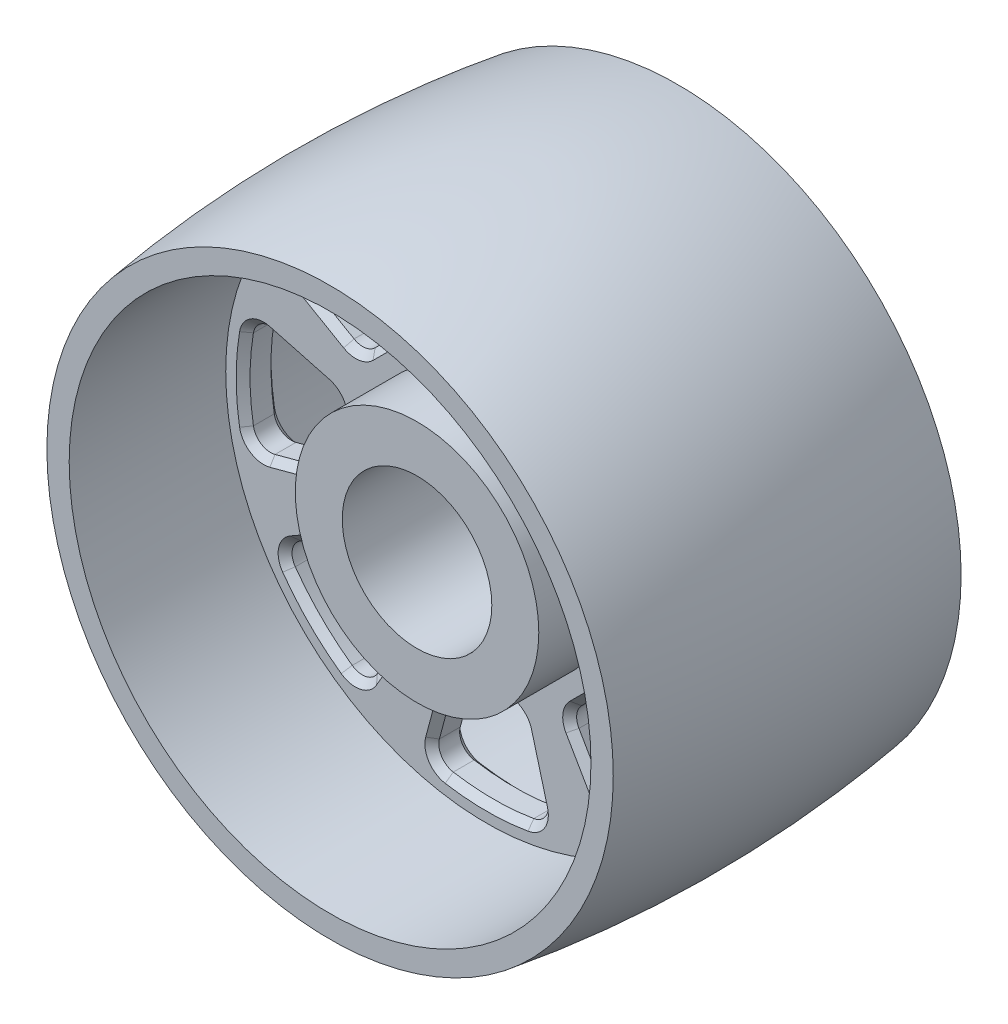
SolidWorks part; units mm, degrees
ref_plane "Front Plane" through (0, 0, 0) normal (0, 0, 1) x (1, 0, 0)
ref_plane "Top Plane" through (0, 0, 0) normal (0, 1, 0) x (1, 0, 0)
ref_plane "Right Plane" through (0, 0, 0) normal (1, 0, 0) x (0, 0, -1)
sketch "Sketch1" plane through (0, 0, 0) normal (1, 0, 0) x (0, 0, -1)
  line L0 (0, 0) -> (340.7129, 0) construction
  line L1 (0, 0) -> (0, 245.6893) construction
  line L2 (-50, 43) -> (50, 43)
  line L3 (-50, 43) -> (-50, 70)
  line L4 (-50, 70) -> (-10, 70)
  line L5 (-10, 70) -> (-10, 150)
  line L6 (-10, 150) -> (-100, 150)
  line L7 (-100, 150) -> (-100, 162.8203)
  line L8 (50, 43) -> (50, 70)
  line L9 (50, 70) -> (10, 70)
  line L10 (10, 70) -> (10, 150)
  line L11 (10, 150) -> (100, 150)
  line L12 (100, 150) -> (100, 162.8203)
  arc A0 (-100, 162.8203) -> (100, 162.8203) centre (0, -530) cw
  point P16 (460.3081, 0)
  point P18 (0, 186.2173)
  point P19 (0, 547.8249)
  point P20 (-100, 156.4102)
  point P21 (-10, 150)
  point P22 (0, 245.6893)
  point P23 (293.5719, 0)
  point P24 (340.7129, 0)
  dimension "D4" = 700
  dimension "D1" = 43
  dimension "D2" = 100
  dimension "D3" = 70
  dimension "D5" = 200
  dimension "D6" = 20
  dimension "D7" = 150
  dimension "D8" = 170
revolve "Revolve1" add sketch "Sketch1" angle 360 about L0
sketch "Sketch3" plane through (0, 0, 10) normal (0, 0, 1) x (1, 0, 0)
  line L0 (0, 0) -> (0, 150) construction
  line L1 (-20, 84) -> (20, 84)
  line L2 (-33.8895, 135.8363) -> (-20, 84)
  line L3 (33.8895, 135.8363) -> (20, 84)
  circle A1 centre (0, 0) radius 150 construction
  arc A2 (-33.8895, 135.8363) -> (33.8895, 135.8363) centre (0, 0) cw
  dimension "D3" = 140
  dimension "D1" = 40
  dimension "D2" = 84
  dimension "D4" = 30
extrude "Cut-Extrude1" cut sketch "Sketch3" against normal up to next
fillet "Fillet1" radius 10 4 edges at (20, 84, 0) (-20, 84, 0) (33.8895, 135.8363, 0) (-33.8895, 135.8363, 0)
chamfer "Chamfer1" distance 4 angle 45 16 edges at (26.5694, 108.5172, -10) (18.4143, 86.0665, -10) (29.9047, 133.6194, -10) (0, 84, -10) (0, 140, -10) (-18.4143, 86.0665, -10) (-29.9047, 133.6194, -10) (-26.5694, 108.5172, -10) (26.5694, 108.5172, 10) (29.9047, 133.6194, 10) (18.4143, 86.0665, 10) (0, 140, 10) (0, 84, 10) (-29.9047, 133.6194, 10) (-18.4143, 86.0665, 10) (-26.5694, 108.5172, 10)
pattern_circular "CirPattern1" count 8 over 360 about axis through (0, 0, 0) along (0, 0, 1) of "Cut-Extrude1", "Fillet1", "Chamfer1"
